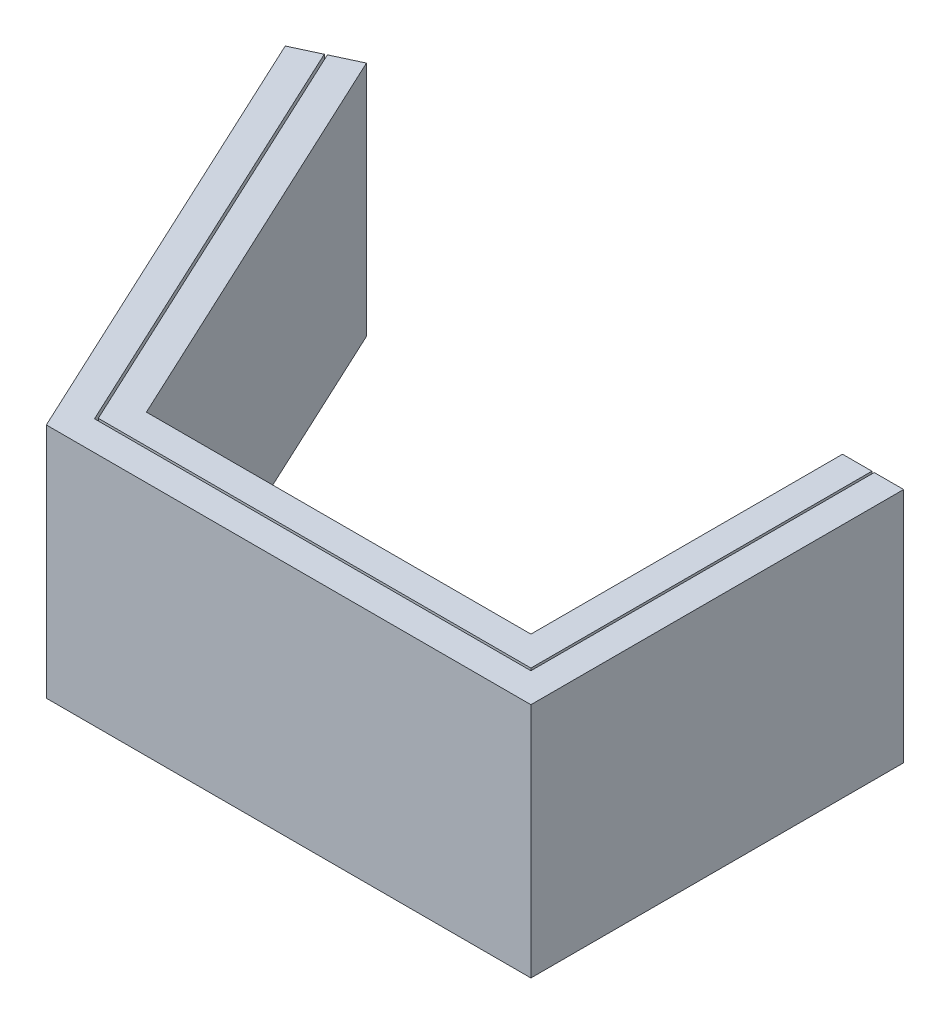
SolidWorks part; units mm, degrees
ref_plane "Alzado" through (0, 0, 0) normal (0, 0, 1) x (1, 0, 0)
ref_plane "Planta" through (0, 0, 0) normal (0, 1, 0) x (1, 0, 0)
ref_plane "Vista lateral" through (0, 0, 0) normal (1, 0, 0) x (0, 0, -1)
sketch "Croquis1" plane through (0, 0, 0) normal (0, 1, 0) x (1, 0, 0)
  line L0 (0, 0) -> (-104, 0)
  line L1 (-104, 0) -> (-148.7975, 96.0686)
  line L2 (0, 0) -> (0, 80)
  line L3 (-6.31, 6.31) -> (-6.31, 80)
  line L4 (-6.31, 6.31) -> (-99.9801, 6.31)
  line L5 (-99.9801, 6.31) -> (-143.0787, 98.7353)
  line L6 (-143.0787, 98.7353) -> (-148.7975, 96.0686)
  line L7 (-6.31, 80) -> (0, 80)
  dimension "D1" = 104
  dimension "D2" = 106
  dimension "D3" = 80
  dimension "D4" = 115
  dimension "D5" = 6.31
extrude "Saliente-Extruir1" add sketch "Croquis1" along normal blind 50.8
sketch "Croquis2" plane through (0, 50.8, 0) normal (0, 1, 0) x (1, 0, 0)
  line L0 (-143.0787, 98.7353) -> (-99.9801, 6.31) construction
  line L1 (-99.9801, 6.31) -> (-6.31, 6.31) construction
  line L2 (-6.31, 6.31) -> (-6.31, 80) construction
  line L3 (-142.6256, 98.9467) -> (-99.6616, 6.81)
  line L4 (-99.6616, 6.81) -> (-6.81, 6.81)
  line L5 (-6.81, 6.81) -> (-6.81, 80)
  line L6 (-136.9068, 101.6134) -> (-95.6416, 13.12)
  line L7 (-95.6416, 13.12) -> (-13.12, 13.12)
  line L8 (-13.12, 13.12) -> (-13.12, 80)
  line L9 (-142.6256, 98.9467) -> (-136.9068, 101.6134)
  line L10 (-13.12, 80) -> (-6.81, 80)
  dimension "D1" = 0.5
  dimension "D2" = 6.31
extrude "Saliente-Extruir2" add sketch "Croquis2" against normal blind 50.8 separate body
